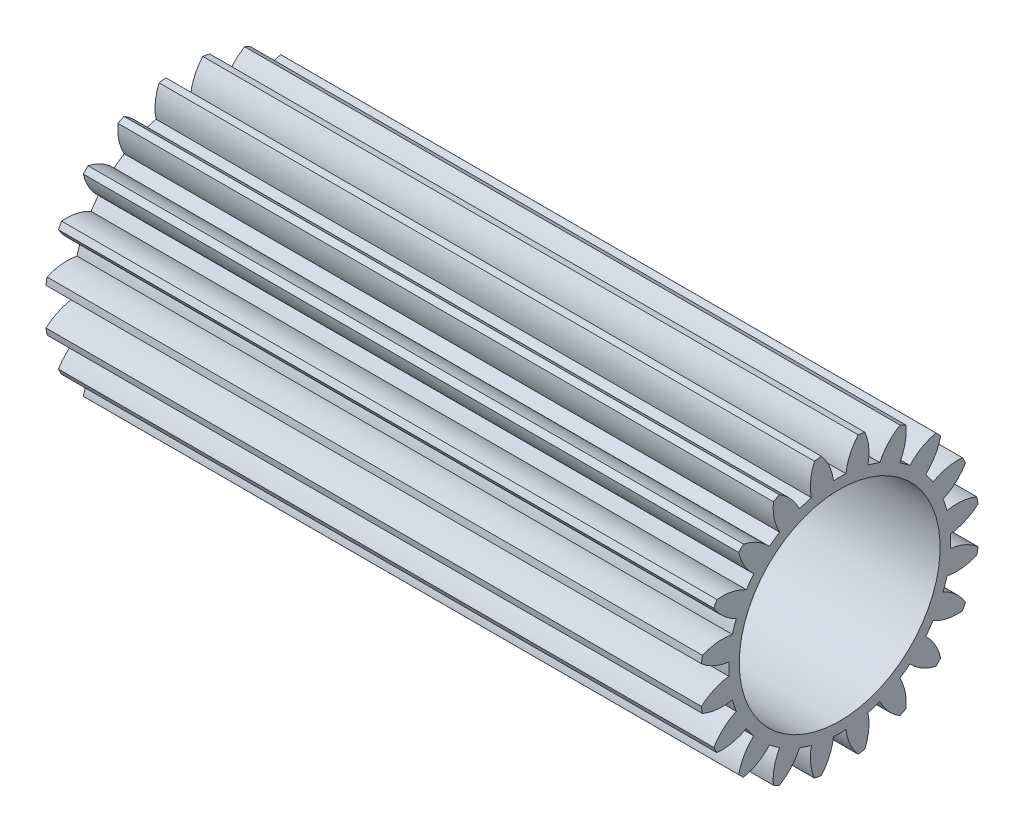
SolidWorks part; units mm, degrees
ref_plane "Plane1" through (0, 0, 0) normal (0, 0, 1) x (1, 0, 0)
ref_plane "Plane2" through (0, 0, 0) normal (0, 1, 0) x (1, 0, 0)
ref_plane "Plane3" through (0, 0, 0) normal (1, 0, 0) x (0, 0, -1)
sketch "HoldingSke" plane through (0, 0, 0) normal (0, 1, 0) x (1, 0, 0)
  line L0 (0, 0) -> (3.1323, -1.1401)
  line L1 (-15, 0) -> (100, 0) construction
  line L2 (0, 0) -> (-2.1039, 2.3779)
  line L3 (0, 0) -> (-11.863, 4.5341)
  line L4 (0, 0) -> (8.1152, 2.9537)
  line L5 (0, 0) -> (-46.8476, -17.4728)
  line L6 (0, 0) -> (-12.8489, -8.6692)
  line L7 (-2.1039, 2.3779) -> (8.6586, 51.2059)
  line L8 (-76.2, 54.61) -> (-75.9, 54.61)
  line L9 (-71.009, 38.7566) -> (-53.1078, 45.2721)
  line L10 (-76.2, 71.12) -> (104.1128, 71.12)
  line L11 (0, 0) -> (-15.5, 0)
  line L12 (-76.2, 101.6) -> (-76.19, 101.6)
  line L13 (24.9733, 27.94) -> (52.9518, 28.4284)
  line L14 (24.9733, 27.94) -> (24.9743, 27.94)
  line L15 (24.9733, 27.94) -> (100.4006, 29.5858)
  line L16 (-63.627, -0.3) -> (-12.827, -0.3)
  circle A0 centre (0, 0) radius 1
  circle A1 centre (0, 0) radius 2.624
  circle A2 centre (0, 0) radius 37.5
  circle A3 centre (0, 0) radius 1
  dimension "MHD" = 5.248
  dimension "Hub_dia" = 75
  dimension "Bore" = 2
  dimension "MBD" = 2
  dimension "Num_teeth" = 20
  dimension "Pitch" = 3.3333
  dimension "Overall_len" = 50
  dimension "Show_teeth" = 20
  dimension "Thickness" = 15.5
  dimension "OAL" = 50.0001
  dimension "T_dim" = 0.3
  dimension "Ap" = 20
  dimension "H" = 19.05
  dimension "Pitch_radius" = 180.3128
  dimension "Width" = 15.5
  dimension "Backlash" = 0.01
  dimension "Addendum_fac" = 1
  dimension "Dedendum_fac" = 1.25
  dimension "Clearance_fac" = 0.25
  dimension "Dedendum_add" = 0.001
  dimension "Module" = 0.3
sketch "BasProSke" plane through (0, 0, 0) normal (0, 1, 0) x (1, 0, 0)
  line L0 (-10, 0) -> (60, 0) construction
  line L1 (0, 0) -> (0, 3.3)
  line L2 (0, 0) -> (15.5, 0)
  line L3 (15.5, 0) -> (15.5, 3.3)
  line L4 (15.5, 3.3) -> (0, 3.3)
  dimension "Thickness" = 15.5
  dimension "Diameter" = 6.6
revolve "Base-Revolve" add sketch "BasProSke" angle 360 about L0
sketch "TooCutSke" plane through (0, 0, 0) normal (1, 0, 0) x (0, 0, -1)
  line L1 (0, 0) -> (0, 107) construction
  line L2 (0, 0) -> (-0.2529, 2.9893) construction
  line L3 (0, 0) -> (-0.9361, 5.9105) construction
  line L4 (-0.2529, 2.9893) -> (-0.4681, 2.9552) construction
  arc A0 (0.1477, 2.6198) -> (-0.1477, 2.6198) centre (0, 0) ccw
  arc A1 (0.4573, 3.2938) -> (-0.4573, 3.2938) centre (0, 0) ccw
  circle A2 centre (0, 0) radius 3 construction
  circle A3 centre (0, 0) radius 2.8191 construction
  arc A4 (-0.1477, 2.6198) -> (-0.4573, 3.2938) centre (-1.3396, 2.4804) ccw
  arc A5 (0.4573, 3.2938) -> (0.1477, 2.6198) centre (1.3396, 2.4804) ccw
  dimension "Root_dia" = 5.248
  dimension "Overcut_dia" = 6.6508
  dimension "Pitch_dia" = 6
  dimension "Base_dia" = 5.6382
  dimension "Flank_rad" = 1.2
  dimension "Half_ang" = 9
  dimension "Half_CT" = 0.2179
extrude "ToothCut" cut sketch "TooCutSke" along normal through all
fillet "Breaks" [suppressed] radius 0.006
fillet "RootFillets" [suppressed] radius 0.076
pattern_circular "TeethCuts" count 20 every 18 about axis through (-10, 0, 0) along (1, 0, 0) of "ToothCut", "RootFillets", "Breaks"
sketch "HubNeaOneSke" plane through (0, 0, 0) normal (-1, 0, 0) x (0, 0, 1)
  circle A0 centre (0, 0) radius 2.624
  dimension "Diameter" = 5.248
extrude "HubNearOne" [suppressed] add sketch "HubNeaOneSke" along normal blind 34.5001
sketch "HubNeaBotSke" plane through (0, 0, 0) normal (-1, 0, 0) x (0, 0, 1)
  circle A0 centre (0, 0) radius 2.624
  dimension "Diameter" = 5.248
extrude "HubNearBoth" [suppressed] add sketch "HubNeaBotSke" along normal blind 17.25
ref_plane "FarPln" through (15.5, 0, 0) normal (1, 0, 0) x (0, 0, -1)
sketch "HubFarSke" plane through (15.5, 0, 0) normal (1, 0, 0) x (0, 0, -1)
  circle A0 centre (0, 0) radius 2.624
  dimension "Diameter" = 5.248
extrude "HubFar" [suppressed] add sketch "HubFarSke" along normal blind 17.25
sketch "BorSke" plane through (0, 0, 0) normal (1, 0, 0) x (0, 0, -1)
  circle A0 centre (0, 0) radius 2.375
  dimension "Diameter" = 4.75
extrude "Bore" cut sketch "BorSke" along normal mid plane 100.0001
sketch "KeySke" plane through (0, 0, 0) normal (1, 0, 0) x (0, 0, -1)
  line L0 (-0.4, 0) -> (-0.4, 1.3)
  line L1 (-0.4, 1.3) -> (0.4, 1.3)
  line L2 (0.4, 1.3) -> (0.4, 0)
  line L3 (0, 0) -> (0, 34) construction
  line L4 (-0.4, 0) -> (0.4, 0)
  dimension "Offset" = 1.3
  dimension "Width" = 0.8
extrude "Keyway" [suppressed] cut sketch "KeySke" along normal mid plane 100.0001
pattern_circular "Keyway2" [suppressed] count 2 every 90 about axis through (-10, 0, 0) along (1, 0, 0)
equation "' \"Module@HoldingSke\" = 6.35"
equation "' \"Num_teeth@HoldingSke\" = 12"
equation "' \"Ap@HoldingSke\" =  20"
equation "' \"Ap@HoldingSke\" = 20"
equation "' \"Width@HoldingSke\" = 0.5 * 25.4"
equation "' \"Hub_dia@HoldingSke\"= 1 * 25.4"
equation "' \"Hub_dia@HoldingSke\" = 1 * 25.4"
equation "' \"Overall_len@HoldingSke\" = 1.0 * 25.4"
equation "' \"Bore@HoldingSke\" = 0.75 * 25.4"
equation "' \"T_dim@HoldingSke\" = 0.1 * 25.4"
equation "' \"Width@KeySke\" = 0.25 * 25.4"
equation "' \"Show_teeth@HoldingSke\" = 13"
equation "' \"Backlash@HoldingSke\" = 0.009 * 25.4"
equation "' \"Addendum_fac@HoldingSke\" = 1.0"
equation "' \"Dedendum_fac@HoldingSke\" = 1.25"
equation "' \"Dedendum_add@HoldingSke\" = 0.00005 * 25.4"
equation "' \"Clearance_fac@HoldingSke\" = 0.25"
equation "\"Pitch@HoldingSke\" = 1 / \"Module@HoldingSke\""
equation "\"Overcut_dia@TooCutSke\" = (\"Num_teeth@HoldingSke\" + 2 * \"Addendum_fac@HoldingSke\") / \"Pitch@HoldingSke\" + 0.002 * 25.4"
equation "\"Pitch_dia@TooCutSke\" = \"Num_teeth@HoldingSke\" / \"Pitch@HoldingSke\""
equation "\"Base_dia@TooCutSke\" = \"Num_teeth@HoldingSke\" / \"Pitch@HoldingSke\" * cos((\"Ap@HoldingSke\"  * 3.14159265 / 180))"
equation "\"Root_dia@TooCutSke\" = (\"Num_teeth@HoldingSke\" + 2) / \"Pitch@HoldingSke\" - 2 * (\"Addendum_fac@HoldingSke\" + \"Dedendum_fac@HoldingSke\") / \"Pitch@HoldingSke\" - \"Dedendum_add@HoldingSke\" * 2"
equation "\"Half_ang@TooCutSke\" = 180 / \"Num_teeth@HoldingSke\""
equation "\"Half_CT@TooCutSke\" = \"Num_teeth@HoldingSke\" / \"Pitch@HoldingSke\" * sin((3.14159265 / 2 / \"Num_teeth@HoldingSke\")) / 2 - 7 * \"Backlash@HoldingSke\" / 4"
equation "\"Flank_rad@TooCutSke\" = \"Num_teeth@HoldingSke\" / \"Pitch@HoldingSke\" / 5"
equation "\"Radius@RootFillets\" = \"Clearance_fac@HoldingSke\" / \"Pitch@HoldingSke\" + \"Dedendum_add@HoldingSke\""
equation "\"Break_rad@Breaks\" = 0.02 / \"Pitch@HoldingSke\""
equation "\"Thickness@HoldingSke\" = \"Width@HoldingSke\""
equation "\"OAL@HoldingSke\" = \"Thickness@HoldingSke\""
equation "\"MHD@HoldingSke\" = (\"Num_teeth@HoldingSke\" + 2) / \"Pitch@HoldingSke\" - 2 * (\"Addendum_fac@HoldingSke\" + \"Dedendum_fac@HoldingSke\")  / \"Pitch@HoldingSke\" - \"Dedendum_add@HoldingSke\" * 2"
equation "\"MBD@HoldingSke\" = (\"Num_teeth@HoldingSke\" + 2) / \"Pitch@HoldingSke\" - 2 * (\"Addendum_fac@HoldingSke\" + \"Dedendum_fac@HoldingSke\")  / \"Pitch@HoldingSke\" - \"Dedendum_add@HoldingSke\" * 2 - 0.002 * 25.4"
equation "\"MHD@HoldingSke\" = ((sgn( \"MHD@HoldingSke\" - \"Hub_dia@HoldingSke\" )-1)*( \"MHD@HoldingSke\" - \"Hub_dia@HoldingSke\" ))/-2+ \"Hub_dia@HoldingSke\""
equation "\"MBD@HoldingSke\" = ((sgn( \"MBD@HoldingSke\" - \"Bore@HoldingSke\" )-1)*( \"MBD@HoldingSke\" - \"Bore@HoldingSke\" ))/-2+ \"Bore@HoldingSke\""
equation "\"OAL@HoldingSke\" = ((sgn( \"OAL@HoldingSke\" - \"Overall_len@HoldingSke\" )+1)*( \"OAL@HoldingSke\" - \"Overall_len@HoldingSke\" ))/2 + \"Overall_len@HoldingSke\" + 0.000002 * 25.4"
equation "\"Num_teeth@TeethCuts\" = int( \"Show_teeth@HoldingSke\" ) + 1"
equation "\"Num_teeth@TeethCuts\" = ((sgn( \"Num_teeth@TeethCuts\" - \"Num_teeth@HoldingSke\" )-1)*( \"Num_teeth@TeethCuts\" - \"Num_teeth@HoldingSke\" ))/-2+ \"Num_teeth@HoldingSke\""
equation "\"Num_teeth@TeethCuts\" = ((sgn( \"Num_teeth@TeethCuts\" - 2.0)+1)*( \"Num_teeth@TeethCuts\" - 2.0))/2 +2.0"
equation "\"Angle@TeethCuts\" = 360.0 / \"Num_teeth@HoldingSke\""
equation "\"Diameter@BasProSke\" = (\"Num_teeth@HoldingSke\" + 2 * \"Addendum_fac@HoldingSke\") / \"Pitch@HoldingSke\""
equation "\"Thickness@BasProSke\"  = \"Thickness@HoldingSke\""
equation "' \"Fillet_rad@BasProSke\" =  \"Thickness@HoldingSke\" * 0.05"
equation "' \"Fillet_rad@BasProSke\" = \"Thickness@HoldingSke\" * 0.05"
equation "\"MHD@HoldingSke\" = ((sgn( \"MHD@HoldingSke\" - \"Root_dia@TooCutSke\" )-1)*( \"MHD@HoldingSke\" - \"Root_dia@TooCutSke\" ))/-2+ \"Root_dia@TooCutSke\""
equation "\"Diameter@HubNeaOneSke\" = \"MHD@HoldingSke\""
equation "\"Length@HubNearOne\" = \"OAL@HoldingSke\" - \"Thickness@BasProSke\""
equation "\"Diameter@HubNeaBotSke\" = \"MHD@HoldingSke\""
equation "\"Length@HubNearBoth\" = ( \"OAL@HoldingSke\" - \"Thickness@BasProSke\" ) / 2.0"
equation "\"Thickness@FarPln\" = \"Thickness@BasProSke\""
equation "\"Diameter@HubFarSke\" = \"MHD@HoldingSke\""
equation "\"Length@HubFar\" = ( \"OAL@HoldingSke\" - \"Thickness@BasProSke\" ) / 2.0"
equation "\"Diameter@BorSke\"=4.75"
equation "\"D1@Bore\" = \"OAL@HoldingSke\" * 2.0"
equation "\"D1@Keyway\" = \"OAL@HoldingSke\" * 2.0"
equation "\"Offset@KeySke\" = \"T_dim@HoldingSke\" + \"MBD@HoldingSke\" / 2.0"
